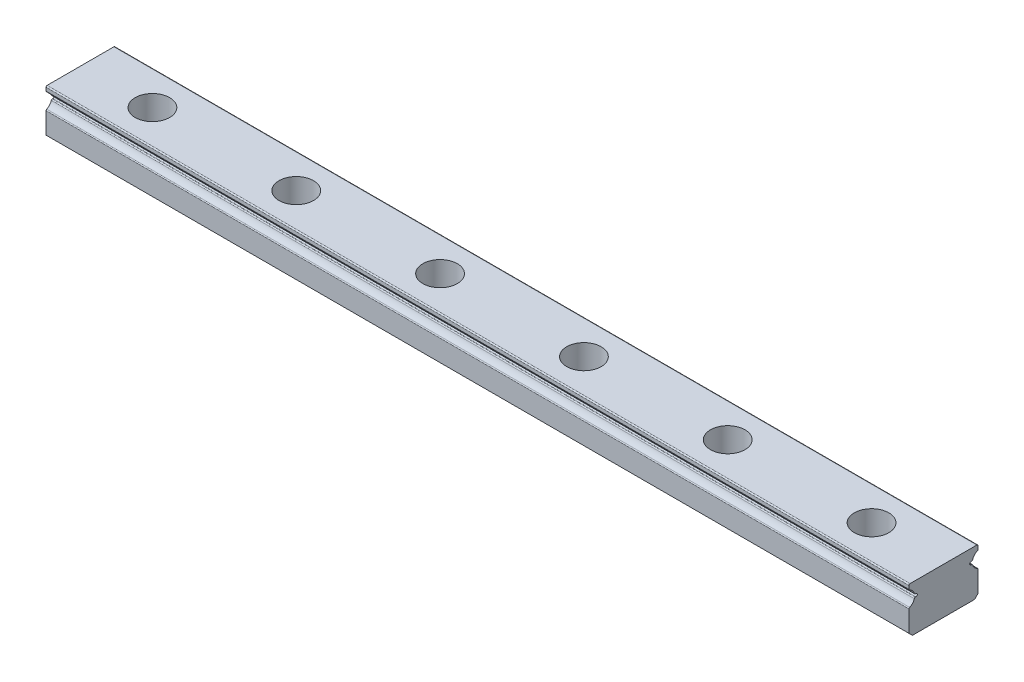
SolidWorks part; units mm, degrees
ref_plane "前视基准面" through (0, 0, 0) normal (0, 0, 1) x (1, 0, 0)
ref_plane "上视基准面" through (0, 0, 0) normal (0, 1, 0) x (1, 0, 0)
ref_plane "右视基准面" through (0, 0, 0) normal (1, 0, 0) x (0, 0, -1)
other "Configuration Table"
ref_plane "基准面1" through (0, 4, 0) normal (0, 1, 0) x (1, 0, 0)
sketch "草图1" plane through (0, 4, 0) normal (0, 1, 0) x (1, 0, 0)
  line L0 (75, -6) -> (75, 6)
  line L1 (75, 6) -> (-75, 6)
  line L2 (-75, 6) -> (-75, -6)
  line L3 (-75, -6) -> (75, -6)
extrude "凸台-拉伸1" add sketch "草图1" against normal blind 8
sketch "草图2" plane through (75, 0, 0) normal (1, 0, 0) x (0, 0, -1)
  line L0 (6, 1.51) -> (6, 2.01)
  line L1 (6, 2.01) -> (4.8, 2.01)
  line L2 (4.8, 1.51) -> (6, 1.51)
  arc A0 (4.8, 2.01) -> (4.8, 1.51) centre (4.8, 1.76) ccw
extrude "切除-拉伸1" cut sketch "草图2" against normal through all
sketch "草图3" plane through (75, 0, 0) normal (1, 0, 0) x (0, 0, -1)
  line L0 (6, 2.01) -> (6, 3.1111)
  line L1 (5.04, 2.01) -> (6, 2.01)
  arc A0 (6, 3.1111) -> (5.04, 2.01) centre (6.4382, 1.76) ccw
extrude "切除-拉伸2" cut sketch "草图3" against normal through all
sketch "草图4" plane through (75, 0, 0) normal (1, 0, 0) x (0, 0, -1)
  line L0 (6, 1.51) -> (5.04, 1.51)
  line L1 (6, 0.4089) -> (6, 1.51)
  arc A0 (5.04, 1.51) -> (6, 0.4089) centre (6.4382, 1.76) ccw
extrude "切除-拉伸3" cut sketch "草图4" against normal through all
sketch "草图5" plane through (75, 0, 0) normal (1, 0, 0) x (0, 0, -1)
  line L0 (-6, 2.01) -> (-6, 1.51)
  line L1 (-6, 1.51) -> (-4.8, 1.51)
  line L2 (-4.8, 2.01) -> (-6, 2.01)
  arc A0 (-4.8, 1.51) -> (-4.8, 2.01) centre (-4.8, 1.76) ccw
extrude "切除-拉伸4" cut sketch "草图5" against normal through all
sketch "草图6" plane through (75, 0, 0) normal (1, 0, 0) x (0, 0, -1)
  line L0 (-6, 1.51) -> (-6, 0.4089)
  line L1 (-5.04, 1.51) -> (-6, 1.51)
  arc A0 (-6, 0.4089) -> (-5.04, 1.51) centre (-6.4382, 1.76) ccw
extrude "切除-拉伸5" cut sketch "草图6" against normal through all
sketch "草图7" plane through (75, 0, 0) normal (1, 0, 0) x (0, 0, -1)
  line L0 (-6, 2.01) -> (-5.04, 2.01)
  line L1 (-6, 3.1111) -> (-6, 2.01)
  arc A0 (-5.04, 2.01) -> (-6, 3.1111) centre (-6.4382, 1.76) ccw
extrude "切除-拉伸6" cut sketch "草图7" against normal through all
hole_wizard "M3 六角头机械螺钉的柱形沉头孔1" positions "草图9" profile "草图8" counterbore size "M3" standard "ANSI Metric"
sketch "草图9" plane through (0, 4, 0) normal (0, 1, 0) x (1, 0, 0)
  point P0 (-62.5, 0)
  point P1 (-37.5, 0)
  point P2 (-12.5, 0)
  point P3 (12.5, 0)
  point P4 (37.5, 0)
  point P5 (62.5, 0)
sketch "草图8" plane through (-62.5, 4, 0) normal (1, 0, 0) x (0, 0, 1)
  line L0 (0, 0) -> (0, 8)
  line L1 (0, 8) -> (1.75, 8)
  line L3 (1.75, 8) -> (1.75, 4.5)
  line L4 (1.75, 4.5) -> (2.9999, 4.5)
  line L5 (2.9999, 4.5) -> (2.9999, 0)
  line L7 (2.9999, 0) -> (0, 0)
  line L11 (0, -6.35) -> (0, 107.95) construction
  dimension "通孔孔直径" = 3.5
  dimension "通孔孔深度" = 8
  dimension "柱形沉头孔直径" = 5.9999
  dimension "柱形沉头孔深度" = 4.5
chamfer "倒角1" distance 0.6 angle 45 2 edges at (0, -4, -6) (0, -4, 6)
fillet "圆角1" radius 0.2 10 edges at (0, 3.1111, -6) (0, 1.51, -5.04) (0, 4, -6) (0, 1.51, 5.04) (0, 2.01, -5.04) (0, 2.01, 5.04) (0, 4, 6) (0, 3.1111, 6) (0, 0.4089, -6) (0, 0.4089, 6)
